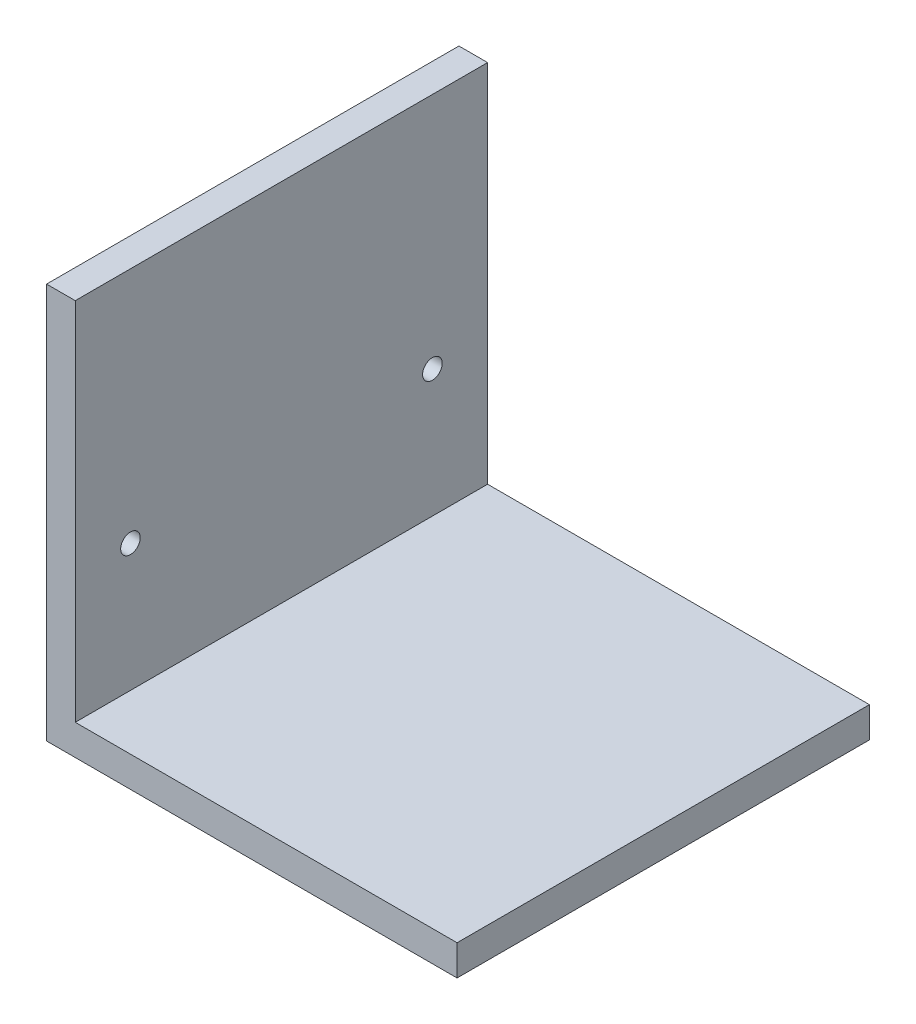
SolidWorks part; units mm, degrees
ref_plane "Front Plane" through (0, 0, 0) normal (0, 0, 1) x (1, 0, 0)
ref_plane "Top Plane" through (0, 0, 0) normal (0, 1, 0) x (1, 0, 0)
ref_plane "Right Plane" through (0, 0, 0) normal (1, 0, 0) x (0, 0, -1)
sketch "Sketch1" plane through (0, 0, 0) normal (1, 0, 0) x (0, 0, -1)
  line L0 (55, 0) -> (-55, 0) construction
  line L1 (-21.06, 0) -> (21.06, 0)
  line L2 (-21.06, 0) -> (-21.06, 40.42)
  line L3 (-21.06, 40.42) -> (21.06, 40.42)
  line L4 (21.06, 0) -> (21.06, 40.42)
  point P6 (0, 0)
  dimension "D1" = 40.42
  dimension "D2" = 42.12
extrude "Boss-Extrude1" add sketch "Sketch1" along normal blind 0.01
sketch "Sketch2" plane through (0.01, 0, 0) normal (1, 0, 0) x (0, 0, -1)
  line L0 (55, 0) -> (-55, 0) construction
  line L1 (-21.06, 0) -> (21.06, 0)
  line L2 (-21.06, 0) -> (-21.06, 40.42)
  line L3 (-21.06, 40.42) -> (21.06, 40.42)
  line L4 (21.06, 0) -> (21.06, 40.42)
  line L5 (21.06, 0) -> (21.06, 40.42) construction
  line L6 (-21.06, 40.42) -> (-21.06, 0) construction
  dimension "D1" = 40.42
extrude "Boss-Extrude2" add sketch "Sketch2" along normal blind 2.92
sketch "Sketch3" plane through (2.93, 0, 0) normal (1, 0, 0) x (0, 0, -1)
  line L0 (55, 0) -> (-55, 0) construction
  line L1 (-21.06, 0) -> (21.06, 0)
  line L2 (-21.06, 0) -> (-21.06, 3.12)
  line L3 (-21.06, 3.12) -> (21.06, 3.12)
  line L4 (21.06, 0) -> (21.06, 3.12)
  line L5 (-21.06, 40.42) -> (-21.06, 0) construction
  line L6 (21.06, 0) -> (21.06, 40.42) construction
  dimension "D1" = 3.12
extrude "Boss-Extrude3" add sketch "Sketch3" along normal blind 39
sketch "Sketch4" plane through (0, 0, 0) normal (-1, 0, 0) x (0, 0, 1)
  line L0 (1.6115, 0) -> (-1.6115, 0) construction
  line L1 (21.06, 40.42) -> (21.06, 0) construction
  line L2 (0, -1.6115) -> (0, 1.6115) construction
  circle A0 centre (15.42, 16.14) radius 1
  circle A1 centre (-15.42, 16.14) radius 1
  dimension "D2" = 2
  dimension "D1" = 16.14
  dimension "D3" = 5.64
extrude "Cut-Extrude1" cut sketch "Sketch4" against normal through all
sketch "Sketch5" plane through (0, 0, 0) normal (0, -1, 0) x (1, 0, 0)
  line L0 (22.231, 0) -> (-22.231, 0) construction
  line L1 (41.93, 21.06) -> (41.93, -21.06) construction
  circle A0 centre (25.93, 0) radius 9.088
  dimension "D1" = 16
extrude "Cut-Extrude2" cut sketch "Sketch5" against normal blind 1
